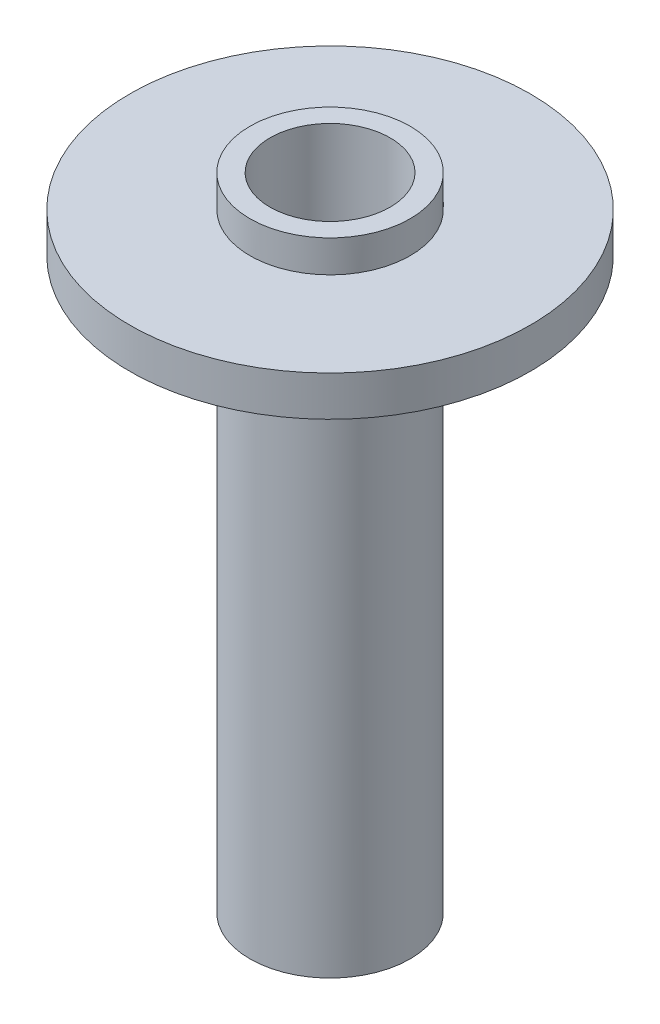
SolidWorks part; units mm, degrees
ref_plane "Front Plane" through (0, 0, 0) normal (0, 0, 1) x (1, 0, 0)
ref_plane "Top Plane" through (0, 0, 0) normal (0, 1, 0) x (1, 0, 0)
ref_plane "Right Plane" through (0, 0, 0) normal (1, 0, 0) x (0, 0, -1)
sketch "Sketch1" plane through (0, 0, 0) normal (0, 1, 0) x (1, 0, 0)
  circle A0 centre (0, 0) radius 10
  circle A1 centre (0, 0) radius 7.5
  dimension "D1" = 20
  dimension "D2" = 15
extrude "Boss-Extrude1" add sketch "Sketch1" along normal blind 80 contours A0 | A1
sketch "Sketch2" plane through (0, 0, 0) normal (1, 0, 0) x (0, 0, -1)
  line L0 (10, 0) -> (10, 80) construction
  line L1 (10, 76) -> (25, 76)
  line L2 (10, 76) -> (10, 71)
  line L3 (10, 71) -> (25, 71)
  line L4 (25, 76) -> (25, 71)
  line L5 (7.5, 80) -> (-7.5, 80) construction
  line L6 (0, 0) -> (0, 80) construction
  line L7 (10, 80) -> (-10, 80) construction
  dimension "D1" = 15
  dimension "D2" = 5
  dimension "D3" = 4
revolve "Revolve1" add sketch "Sketch2" angle 360 about L6
